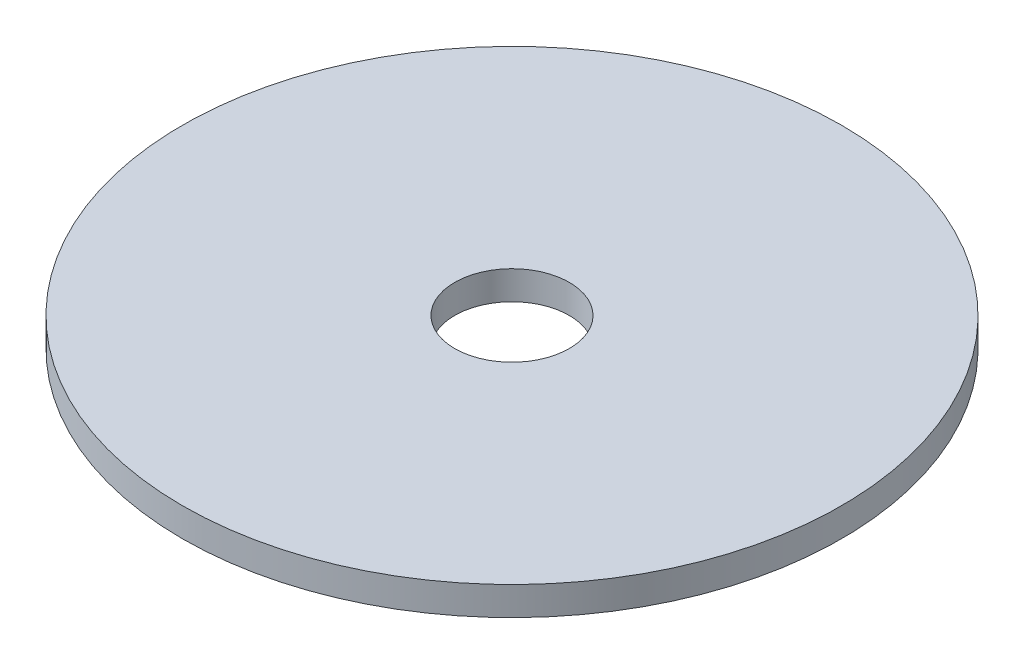
SolidWorks part; units mm, degrees
material "Plastique personnalisé"
ref_plane "Plan de face" through (0, 0, 0) normal (0, 0, 1) x (1, 0, 0)
ref_plane "Plan de dessus" through (0, 0, 0) normal (0, 1, 0) x (1, 0, 0)
ref_plane "Plan de droite" through (0, 0, 0) normal (1, 0, 0) x (0, 0, -1)
sketch "Esquisse1" plane through (0, 0, 0) normal (0, 1, 0) x (1, 0, 0)
  circle A0 centre (0, 0) radius 46
  dimension "D1" = 92
extrude "Boss.-Extru.1" add sketch "Esquisse1" along normal blind 4
sketch "Esquisse2" plane through (0, 4, 0) normal (0, 1, 0) x (1, 0, 0)
  circle A0 centre (0, 0) radius 8
  dimension "D1" = 16
extrude "Enlèv. mat.-Extru.1" cut sketch "Esquisse2" against normal blind 4.5 contours A0
ref_plane "Plan1" through (0, 0, 0) normal (0, -1, 0) x (-1, 0, 0)
sketch "Esquisse3" plane through (0, 0, 0) normal (0, -1, 0) x (-1, 0, 0)
  arc A0 (0, -32) -> (32, 0) centre (0, 0) ccw
  arc A1 (0, -32) -> (-32, 0) centre (0, 0) cw
  arc A2 (-30, 0) -> (30, 0) centre (0, 0) ccw
  arc A3 (-32, 0) -> (-30, 0) centre (-31, 0) cw
  arc A4 (32, 0) -> (30, 0) centre (31, -0.0854) ccw
  dimension "D2" = 60
  dimension "D1" = 32
extrude "Enlèv. mat.-Extru.2" cut sketch "Esquisse3" against normal blind 2 contours A0 A4 A2 A3 A1
